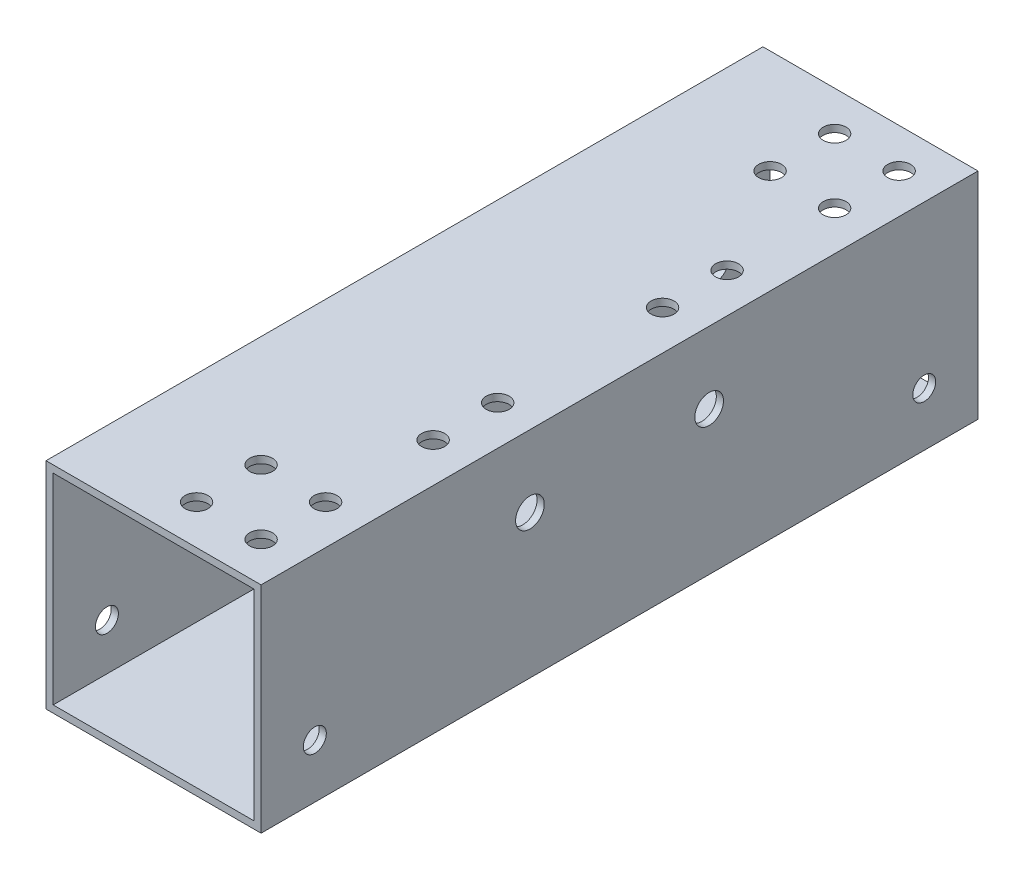
SolidWorks part; units mm, degrees
material "6061-T6 (SS)"
ref_plane "前视基准面" through (0, 0, 0) normal (0, 0, 1) x (1, 0, 0)
ref_plane "上视基准面" through (0, 0, 0) normal (0, 1, 0) x (1, 0, 0)
ref_plane "右视基准面" through (0, 0, 0) normal (1, 0, 0) x (0, 0, -1)
sketch "草图1" plane through (0, 0, 0) normal (0, 0, 1) x (1, 0, 0)
  line L1 (-15, 15) -> (15, 15)
  line L2 (-15, 15) -> (-15, -15)
  line L3 (-15, -15) -> (15, -15)
  line L4 (15, 15) -> (15, -15)
  line L5 (-15, 15) -> (15, -15) construction
  line L6 (-15, -15) -> (15, 15) construction
  line L7 (-14, 14) -> (14, 14)
  line L8 (-14, 14) -> (-14, -14)
  line L9 (-14, -14) -> (14, -14)
  line L10 (14, 14) -> (14, -14)
  line L11 (-14, 14) -> (14, -14) construction
  line L12 (-14, -14) -> (14, 14) construction
  point P0 (0, 0)
  point P6 (0, 0)
  dimension "D1" = 30
  dimension "D2" = 30
  dimension "D3" = 28
  dimension "D4" = 28
extrude "凸台-拉伸1" add sketch "草图1" along normal blind 100
sketch "草图3" plane through (0, 15, 0) normal (0, 1, 0) x (1, 0, 0)
  line L1 (15, -100) -> (-5, -100) construction
  line L2 (15, -100) -> (15, -80) construction
  line L3 (15, -80) -> (-5, -80) construction
  line L4 (-5, -100) -> (-5, -80) construction
  line L5 (15, -100) -> (-5, -80) construction
  line L6 (15, -80) -> (-5, -100) construction
  line L7 (0.5, -85.5) -> (9.5, -85.5) construction
  line L8 (0.5, -85.5) -> (0.5, -94.5) construction
  line L9 (0.5, -94.5) -> (9.5, -94.5) construction
  line L10 (9.5, -85.5) -> (9.5, -94.5) construction
  line L11 (0.5, -85.5) -> (9.5, -94.5) construction
  line L12 (0.5, -94.5) -> (9.5, -85.5) construction
  line L13 (-15, 0) -> (15, 0) construction
  line L14 (-15, 0) -> (-15, -100) construction
  line L15 (-15, -100) -> (15, -100) construction
  line L16 (15, 0) -> (15, -100) construction
  line L17 (0, -100) -> (0, 0) construction
  line L18 (-15, -50) -> (15, -50) construction
  circle A0 centre (0.5, -94.5) radius 1.6
  circle A1 centre (9.5, -94.5) radius 1.6
  circle A2 centre (9.5, -85.5) radius 1.6
  circle A3 centre (0.5, -85.5) radius 1.6
  circle A4 centre (9.5, -14.5) radius 1.6
  circle A5 centre (9.5, -5.5) radius 1.6
  circle A6 centre (0.5, -5.5) radius 1.6
  circle A7 centre (0.5, -14.5) radius 1.6
  circle A8 centre (9.5, -70.5) radius 1.6
  circle A9 centre (9.5, -61.5) radius 1.6
  circle A10 centre (9.5, -38.5) radius 1.6
  circle A11 centre (9.5, -29.5) radius 1.6
  point P4 (5, -90)
  point P6 (5, -90)
  point P258 (0, -50)
  dimension "D4" = 2
  dimension "D1" = 20
  dimension "D2" = 20
  dimension "D3" = 9
  dimension "D5" = 2
  dimension "D6" = 2
extrude "切除-拉伸1" cut sketch "草图3" against normal through all
sketch "草图5" plane through (15, 0, 0) normal (1, 0, 0) x (0, 0, -1)
  line L0 (-100, -15) -> (0, -15) construction
  line L1 (-100, 15) -> (-85, 15) construction
  line L2 (-100, 15) -> (-100, -15) construction
  line L3 (-100, -15) -> (-85, -15) construction
  line L4 (-85, 15) -> (-85, -15) construction
  line L5 (-92.5, -15) -> (-92.5, 15) construction
  line L6 (-100, 0) -> (-85, 0) construction
  line L8 (-100, -15) -> (-85, -15) construction
  line L9 (-100, -15) -> (-100, 0) construction
  line L10 (-100, 0) -> (-85, 0) construction
  line L11 (-85, -15) -> (-85, 0) construction
  line L12 (-92.5, 0) -> (-92.5, -15) construction
  line L13 (-100, -7.5) -> (-85, -7.5) construction
  circle A0 centre (-92.5, -7.5) radius 1.6
  circle A1 centre (-7.5, -7.5) radius 1.6
  point P160 (-92.5, -7.5)
  point P196 (-92.5, 0)
  dimension "D3" = 2
  dimension "D1" = 15
  dimension "D2" = 15
extrude "切除-拉伸3" cut sketch "草图5" against normal through all
sketch "草图6" plane through (15, 0, 0) normal (1, 0, 0) x (0, 0, -1)
  line L1 (-100, 15) -> (0, 15) construction
  line L2 (-100, 15) -> (-100, -15) construction
  line L3 (-100, -15) -> (0, -15) construction
  line L4 (0, 15) -> (0, -15) construction
  line L5 (-50, -15) -> (-50, 15) construction
  line L6 (-100, 0) -> (0, 0) construction
  line L7 (-62.5, 5) -> (-37.5, 5) construction
  line L8 (-62.5, 5) -> (-62.5, -5) construction
  line L9 (-62.5, -5) -> (-37.5, -5) construction
  line L10 (-37.5, 5) -> (-37.5, -5) construction
  line L11 (-62.5, 5) -> (-37.5, -5) construction
  line L12 (-62.5, -5) -> (-37.5, 5) construction
  circle A0 centre (-62.5, 5) radius 2
  circle A1 centre (-37.5, 5) radius 2
  point P4 (-50, 0)
  point P364 (-50, 0)
  dimension "D1" = 25
  dimension "D2" = 10
extrude "切除-拉伸4" cut sketch "草图6" against normal through all
sketch "草图7" plane through (0, -15, 0) normal (0, -1, 0) x (1, 0, 0)
  line L1 (-4.5216, 98.5429) -> (13.0528, 98.5429)
  line L2 (-4.5216, 98.5429) -> (-4.5216, 80.7125)
  line L3 (-4.5216, 80.7125) -> (13.0528, 80.7125)
  line L4 (13.0528, 98.5429) -> (13.0528, 80.7125)
  line L5 (4.2656, 80.7125) -> (4.2656, 98.5429) construction
  line L6 (-4.5216, 89.6277) -> (13.0528, 89.6277) construction
  line L7 (-3.7538, 20.0553) -> (13.0528, 20.0553)
  line L8 (-3.7538, 20.0553) -> (-3.7538, 1.2012)
  line L9 (-3.7538, 1.2012) -> (13.0528, 1.2012)
  line L10 (13.0528, 20.0553) -> (13.0528, 1.2012)
  line L11 (4.6495, 1.2012) -> (4.6495, 20.0553) construction
  line L12 (-3.7538, 10.6282) -> (13.0528, 10.6282) construction
  point P68 (4.6495, 10.6282)
  point P76 (4.2656, 89.6277)
extrude "凸台-拉伸2" add sketch "草图7" against normal blind 1
sketch "草图8" plane through (0, -15, 0) normal (0, -1, 0) x (1, 0, 0)
  line L0 (9.5, 70.5) -> (9.5, 61.5) construction
  line L1 (14, 70.5) -> (14, 61.5)
  line L2 (5, 70.5) -> (5, 61.5)
  line L3 (15, 100) -> (15, 0) construction
  line L4 (9.5, 29.5) -> (9.5, 38.5) construction
  line L5 (-15, 0) -> (15, 0) construction
  line L6 (-15, 0) -> (-15, 100) construction
  line L7 (-15, 100) -> (15, 100) construction
  line L8 (15, 0) -> (15, 100) construction
  line L9 (0, 100) -> (0, 0) construction
  line L10 (-15, 50) -> (15, 50) construction
  line L11 (14, 29.5) -> (14, 38.5)
  line L12 (5, 29.5) -> (5, 38.5)
  circle A0 centre (9.5, 70.5) radius 1.6 construction
  arc A1 (14, 70.5) -> (5, 70.5) centre (9.5, 70.5) ccw
  circle A2 centre (9.5, 61.5) radius 1.6 construction
  arc A3 (5, 61.5) -> (14, 61.5) centre (9.5, 61.5) ccw
  arc A4 (14, 29.5) -> (5, 29.5) centre (9.5, 29.5) cw
  arc A5 (5, 38.5) -> (14, 38.5) centre (9.5, 38.5) cw
  point P0 (9.5, 66)
  point P17 (9.5, 34)
  point P179 (0, 50)
  dimension "D1" = 5.5
  dimension "D2" = 9
  dimension "D3" = 9
extrude "切除-拉伸5" cut sketch "草图8" against normal up to next
